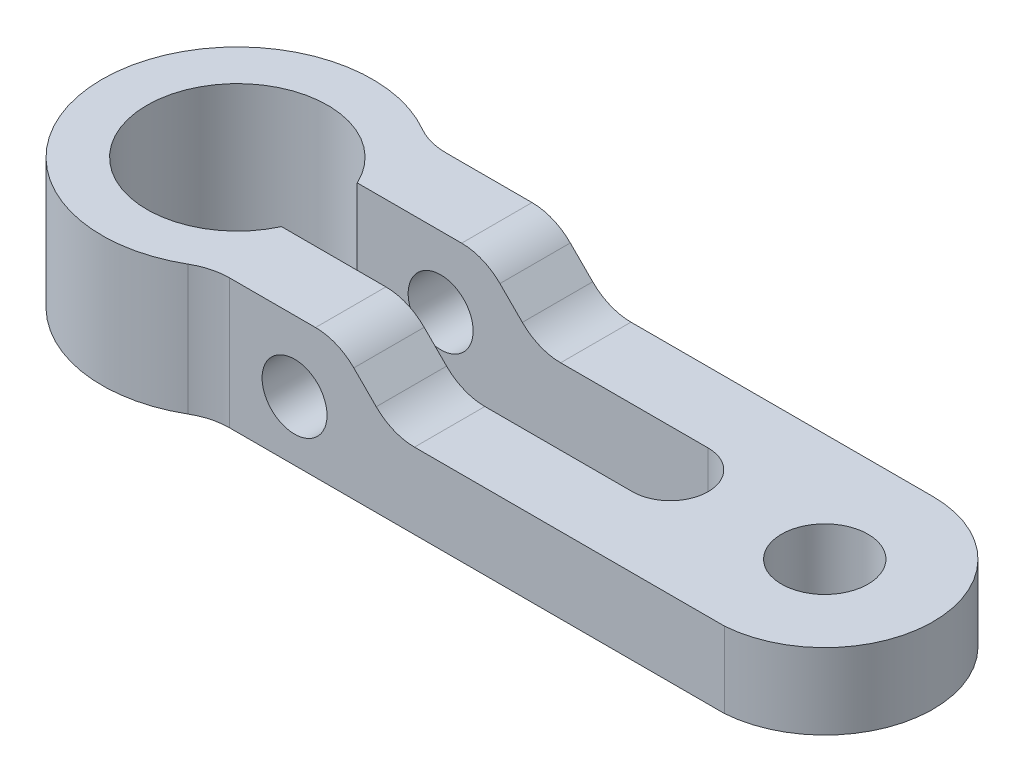
SolidWorks part; units mm, degrees
ref_plane "Front Plane" through (0, 0, 0) normal (0, 0, 1) x (1, 0, 0)
ref_plane "Top Plane" through (0, 0, 0) normal (0, 1, 0) x (1, 0, 0)
ref_plane "Right Plane" through (0, 0, 0) normal (1, 0, 0) x (0, 0, -1)
sketch "Sketch1" plane through (0, 0, 0) normal (0, 1, 0) x (1, 0, 0)
  line L0 (9.2871, 10) -> (54.2871, 10)
  line L2 (55, -10) -> (9.2871, -10)
  arc A0 (6.2751, 10.8108) -> (6.2751, -10.8108) centre (0, 0) ccw
  circle A1 centre (0, 0) radius 8.35
  arc A2 (9.2871, 10) -> (6.2751, 10.8108) centre (9.2871, 16) cw
  arc A3 (9.2871, -10) -> (6.2751, -10.8108) centre (9.2871, -16) ccw
  arc A4 (54.2871, 10) -> (55, -10) centre (54.2871, -0.0127) cw
  circle A5 centre (54.2871, -0.0127) radius 4
  dimension "D1" = 16.7
  dimension "D2" = 25
  dimension "D5" = 6
  dimension "D6" = 10.0127
  dimension "D7" = 8
  dimension "D3" = 45
  dimension "D4" = 20
extrude "Boss-Extrude1" add sketch "Sketch1" along normal blind 12
sketch "Sketch2" plane through (0, 0, 10) normal (0, 0, 1) x (1, 0, 0)
  line L0 (19.2998, 12) -> (24.2998, 7)
  line L1 (9.2871, 12) -> (55, 12) construction
  line L2 (24.2998, 7) -> (64.2998, 7)
  line L3 (64.2998, 0) -> (64.2998, 12) construction
  line L4 (64.2998, 7) -> (64.2998, 12)
  line L5 (64.2998, 12) -> (19.2998, 12)
  line L6 (54.2871, 0) -> (64.2998, 0) construction
  dimension "D1" = 7
  dimension "D2" = 45
  dimension "D3" = 45
extrude "Cut-Extrude1" cut sketch "Sketch2" against normal through all
sketch "Sketch4" plane through (0, 0, 10) normal (0, 0, 1) x (1, 0, 0)
  line L1 (-12.5, 0) -> (6.2751, 0) construction
  line L2 (9.2871, 12) -> (9.2871, 0) construction
  circle A1 centre (15.2871, 5.5) radius 3
  dimension "D1" = 6
  dimension "D3" = 5.5
  dimension "D4" = 6
extrude "Cut-Extrude3" cut sketch "Sketch4" against normal through all
fillet "Fillet2" radius 5 2 edges at (24.2998, 7, 0) (19.2998, 12, 0)
sketch "Sketch5" plane through (0, 12, 0) normal (0, 1, 0) x (1, 0, 0)
  line L1 (0, -3.5) -> (40, -3.5)
  line L2 (0, -3.5) -> (0, 3.5)
  line L3 (0, 3.5) -> (40, 3.5)
  arc A0 (40, 3.5) -> (40, -3.5) centre (40, 0) cw
  dimension "D2" = 40
  dimension "D1" = 7
extrude "Cut-Extrude4" cut sketch "Sketch5" against normal through all both and the other way through all
